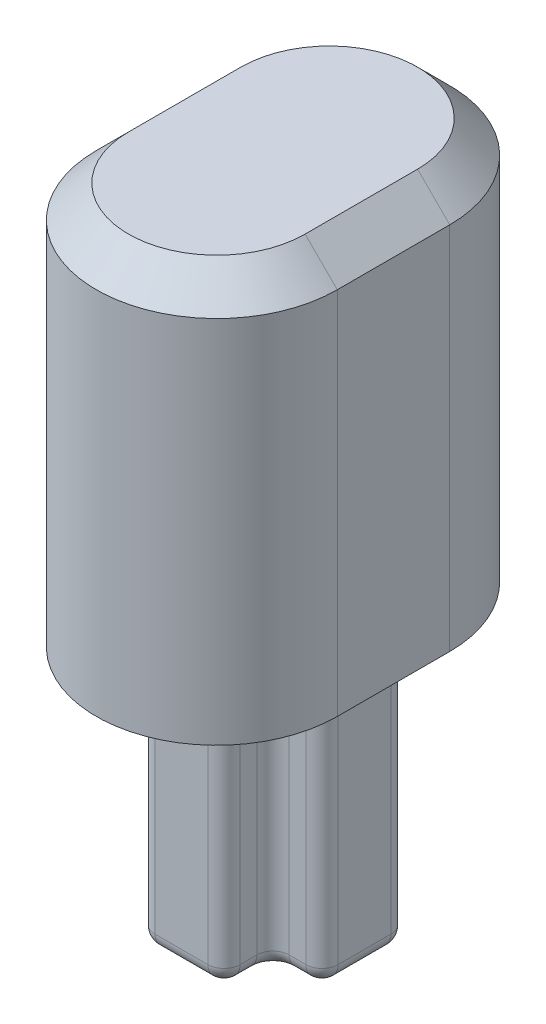
SolidWorks part; units mm, degrees
ref_plane "Front Plane" through (0, 0, 0) normal (0, 0, 1) x (1, 0, 0)
ref_plane "Top Plane" through (0, 0, 0) normal (0, 1, 0) x (1, 0, 0)
ref_plane "Right Plane" through (0, 0, 0) normal (1, 0, 0) x (0, 0, -1)
sketch "Sketch8" plane through (-2.2328, 0, 0.6657) normal (0, -1, 0) x (-1, 0, 0)
  line L0 (-26.6943, -20.8278) -> (-26.6943, -22.3528)
  line L9 (-28.2193, -19.5778) -> (-26.6943, -19.5778)
  line L10 (-28.2193, -19.5778) -> (-28.2193, -20.8278)
  line L11 (-28.2193, -20.8278) -> (-26.6943, -20.8278)
  line L12 (-23.9193, -19.5778) -> (-23.9193, -20.8278)
  line L13 (-28.2193, -19.5778) -> (-23.9193, -20.8278) construction
  line L14 (-28.2193, -20.8278) -> (-23.9193, -19.5778) construction
  line L15 (-26.6943, -18.0528) -> (-25.4443, -18.0528)
  line L16 (-26.6943, -18.0528) -> (-26.6943, -19.5778)
  line L17 (-26.6943, -22.3528) -> (-25.4443, -22.3528)
  line L18 (-25.4443, -18.0528) -> (-25.4443, -19.5778)
  line L19 (-26.6943, -18.0528) -> (-25.4443, -22.3528) construction
  line L20 (-26.6943, -22.3528) -> (-25.4443, -18.0528) construction
  line L21 (-25.4443, -20.8278) -> (-25.4443, -22.3528)
  line L22 (-25.4443, -19.5778) -> (-23.9193, -19.5778)
  line L23 (-25.4443, -20.8278) -> (-23.9193, -20.8278)
  line L25 (-24.7443, -18.8778) -> (-23.2193, -18.8778)
  line L26 (-23.2193, -18.8778) -> (-23.2193, -21.5278)
  line L27 (-24.7443, -21.5278) -> (-23.2193, -21.5278)
  line L28 (-24.7443, -21.5278) -> (-24.7443, -23.0528)
  line L29 (-27.3943, -23.0528) -> (-24.7443, -23.0528)
  line L30 (-27.3943, -21.5278) -> (-27.3943, -23.0528)
  line L31 (-28.9193, -21.5278) -> (-27.3943, -21.5278)
  line L32 (-28.9193, -18.8778) -> (-28.9193, -21.5278)
  line L33 (-28.9193, -18.8778) -> (-27.3943, -18.8778)
  line L34 (-27.3943, -17.3528) -> (-27.3943, -18.8778)
  line L35 (-27.3943, -17.3528) -> (-24.7443, -17.3528)
  line L36 (-24.7443, -17.3528) -> (-24.7443, -18.8778)
  point P0 (-26.0693, -20.2028)
  point P5 (-26.0693, -20.2028)
  point P10 (-26.0693, -20.2028)
  point P35 (4.0539, 0.4)
  point P37 (-23.2193, -20.2028)
  point P38 (-23.2193, -20.2028)
  dimension "D1" = 1.25
  dimension "D2" = 4.3
  dimension "D3" = 1.25
  dimension "D4" = 4.3
  dimension "D5" = 0.7
extrude "Boss-Extrude1" add sketch "Sketch8" along normal blind 8.1
sketch "Sketch9" plane through (0, 0, 0) normal (0, 1, 0) x (-1, 0, 0)
  line L0 (-23.8366, 22.6185) -> (-23.8366, 19.1185) construction
  line L1 (-20.0866, 22.6185) -> (-20.0866, 19.1185)
  line L2 (-27.5866, 22.6185) -> (-27.5866, 19.1185)
  line L3 (-25.1616, 22.1935) -> (-22.5116, 19.5435) construction
  line L15 (-22.5116, 18.0185) -> (-22.5116, 19.5435)
  line L16 (-22.5116, 19.5435) -> (-20.9866, 19.5435)
  line L17 (-20.9866, 19.5435) -> (-20.9866, 22.1935)
  line L18 (-20.9866, 22.1935) -> (-22.5116, 22.1935)
  line L19 (-22.5116, 22.1935) -> (-22.5116, 23.7185)
  line L20 (-22.5116, 23.7185) -> (-25.1616, 23.7185)
  line L21 (-25.1616, 23.7185) -> (-25.1616, 22.1935)
  line L22 (-25.1616, 22.1935) -> (-26.6866, 22.1935)
  line L23 (-26.6866, 22.1935) -> (-26.6866, 19.5435)
  line L24 (-26.6866, 19.5435) -> (-25.1616, 19.5435)
  line L25 (-25.1616, 19.5435) -> (-25.1616, 18.0185)
  line L26 (-25.1616, 18.0185) -> (-22.5116, 18.0185)
  line L27 (-22.5116, 18.0185) -> (-22.5116, 19.5435) construction
  line L28 (-22.5116, 19.5435) -> (-20.9866, 19.5435) construction
  line L29 (-20.9866, 19.5435) -> (-20.9866, 22.1935) construction
  line L30 (-20.9866, 22.1935) -> (-22.5116, 22.1935) construction
  line L31 (-22.5116, 22.1935) -> (-22.5116, 23.7185) construction
  line L32 (-22.5116, 23.7185) -> (-25.1616, 23.7185) construction
  line L33 (-25.1616, 23.7185) -> (-25.1616, 22.1935) construction
  line L34 (-25.1616, 22.1935) -> (-26.6866, 22.1935) construction
  line L35 (-26.6866, 22.1935) -> (-26.6866, 19.5435) construction
  line L36 (-26.6866, 19.5435) -> (-25.1616, 19.5435) construction
  line L37 (-25.1616, 19.5435) -> (-25.1616, 18.0185) construction
  line L38 (-25.1616, 18.0185) -> (-22.5116, 18.0185) construction
  arc A1 (-20.0866, 22.6185) -> (-27.5866, 22.6185) centre (-23.8366, 22.6185) ccw
  arc A2 (-27.5866, 19.1185) -> (-20.0866, 19.1185) centre (-23.8366, 19.1185) ccw
  point P5 (-23.8366, 20.8685)
  point P10 (-23.8366, 20.8685)
  dimension "D1" = 7.5
  dimension "D3" = 3.5
  dimension "D2" = 0
extrude "Boss-Extrude2" add sketch "Sketch9" along normal blind 12.5
fillet "Fillet1" radius 0.5 12 edges at (22.5116, -4.05, 19.5435) (20.9866, -4.05, 19.5435) (20.9866, -4.05, 22.1935) (22.5116, -4.05, 22.1935) (22.5116, -4.05, 23.7185) (25.1616, -4.05, 23.7185) (25.1616, -4.05, 22.1935) (26.6866, -4.05, 22.1935) (26.6866, -4.05, 19.5435) (25.1616, -4.05, 19.5435) (22.5116, -4.05, 18.0185) (25.1616, -4.05, 18.0185)
fillet "Fillet2" radius 0.5 24 edges at (22.5116, 0, 18.781) (22.658, 0, 18.1649) (23.8366, 0, 18.0185) (25.0151, 0, 18.1649) (25.1616, 0, 18.781) (25.308, 0, 19.397) (25.9241, 0, 19.5435) (26.5401, 0, 19.6899) (26.6866, 0, 20.8685) (26.5401, 0, 22.047) (25.9241, 0, 22.1935) (25.308, 0, 22.3399) (25.1616, 0, 22.956) (25.0151, 0, 23.572) (23.8366, 0, 23.7185) (22.658, 0, 23.572) (22.5116, 0, 22.956) (22.3651, 0, 22.3399) (21.7491, 0, 22.1935) (21.133, 0, 22.047) (20.9866, 0, 20.8685) (21.133, 0, 19.6899) (21.7491, 0, 19.5435) (22.3651, 0, 19.397)
fillet "Fillet4" radius 0.5 24 edges at (25.0151, -8.1, 23.572) (25.1616, -8.1, 22.956) (25.308, -8.1, 22.3399) (25.9241, -8.1, 22.1935) (26.5401, -8.1, 22.047) (26.6866, -8.1, 20.8685) (26.5401, -8.1, 19.6899) (25.9241, -8.1, 19.5435) (25.308, -8.1, 19.397) (25.1616, -8.1, 18.781) (25.0151, -8.1, 18.1649) (23.8366, -8.1, 18.0185) (22.658, -8.1, 18.1649) (22.5116, -8.1, 18.781) (22.3651, -8.1, 19.397) (21.7491, -8.1, 19.5435) (21.133, -8.1, 19.6899) (20.9866, -8.1, 20.8685) (21.133, -8.1, 22.047) (21.7491, -8.1, 22.1935) (22.3651, -8.1, 22.3399) (22.5116, -8.1, 22.956) (22.658, -8.1, 23.572) (23.8366, -8.1, 23.7185)
chamfer "Chamfer2" distance 1 angle 45 4 edges at (27.5866, 12.5, 20.8685) (23.8366, 12.5, 15.3685) (23.8366, 12.5, 26.3685) (20.0866, 12.5, 20.8685)
equation "\"baseLength\"= 18"
equation "\"firstLoftL\"= \"baseLength\" - 0.25"
equation "\"topSide\"= \"baseWidth\" - 3"
equation "\"topBtm\"= \"baseLength\" - 6"
equation "\"offset\"= 1"
equation "\"firstLoftH\"= 1.8"
equation "\"secLoftH\"= 9.5"
equation "\"baseWidth\"= 18"
equation "\"firstLoftW\"= \"baseWidth\" - 0.25"
equation "\"surfaceCurve\"= 60"
